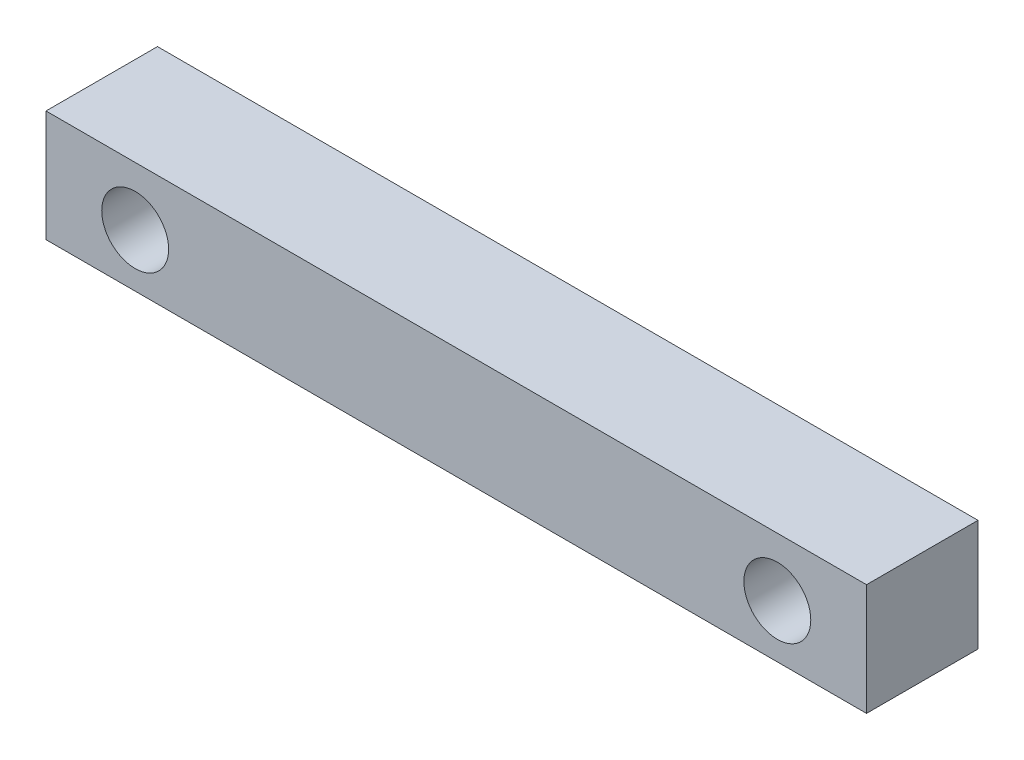
SolidWorks part; units mm, degrees
ref_plane "Front Plane" through (0, 0, 0) normal (0, 0, 1) x (1, 0, 0)
ref_plane "Top Plane" through (0, 0, 0) normal (0, 1, 0) x (1, 0, 0)
ref_plane "Right Plane" through (0, 0, 0) normal (1, 0, 0) x (0, 0, -1)
sketch "Sketch1" plane through (0, 0, 0) normal (0, 0, 1) x (1, 0, 0)
  line L0 (-203.6373, 0) -> (215.2076, 0) construction
  line L1 (0, 149.551) -> (0, -118.5464) construction
  line L3 (-92, -11.8843) -> (92, -11.8843)
  line L4 (-92, -11.8843) -> (-92, 13.1157)
  line L5 (-92, 13.1157) -> (92, 13.1157)
  line L6 (92, -11.8843) -> (92, 13.1157)
  point P5 (0, 0)
  dimension "D1" = 184
  dimension "D2" = 25
extrude "Boss-Extrude1" add sketch "Sketch1" along normal blind 25
sketch "Sketch2" plane through (0, 0, 25) normal (0, 0, 1) x (1, 0, 0)
  line L0 (-115.0097, 0) -> (130.1321, 0) construction
  line L1 (0, 72.0846) -> (0, -72.573) construction
  circle A0 centre (-72, 0) radius 7.5
  circle A1 centre (72, 0) radius 7.5
  dimension "D1" = 15
  dimension "D2" = 15
  dimension "D3" = 144
  dimension "D4" = 72
extrude "Cut-Extrude1" cut sketch "Sketch2" against normal through all both and the other way through all
